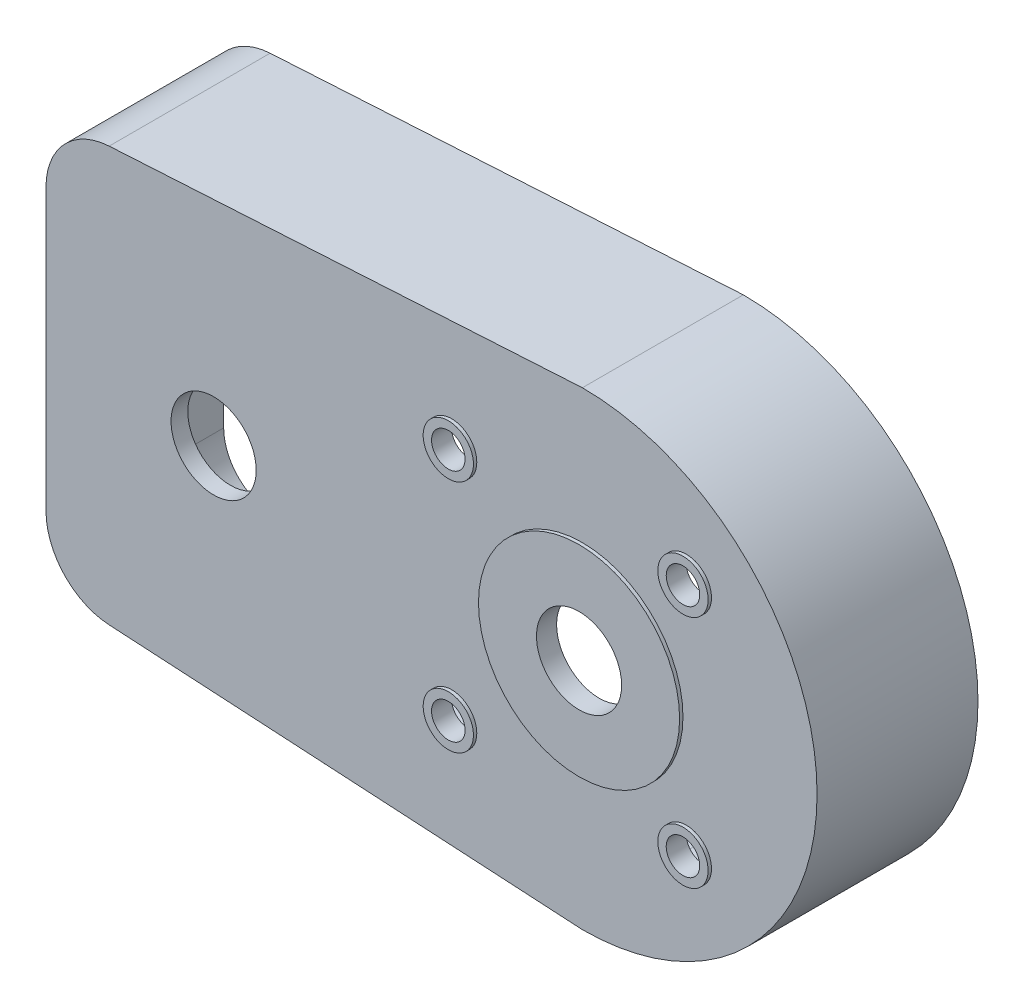
SolidWorks part; units mm, degrees
ref_plane "Front Plane" through (0, 0, 0) normal (0, 0, 1) x (1, 0, 0)
ref_plane "Top Plane" through (0, 0, 0) normal (0, 1, 0) x (1, 0, 0)
ref_plane "Right Plane" through (0, 0, 0) normal (1, 0, 0) x (0, 0, -1)
sketch "Sketch1" plane through (0, 0, 0) normal (0, 0, 1) x (1, 0, 0)
  line L0 (0, 0) -> (230, 0) construction
  line L1 (160, 52.3684) -> (160, -88.6842) construction
  line L2 (0, 41.8729) -> (0, -41.8729)
  line L3 (18.8457, 61.8395) -> (160, 70)
  line L4 (18.8457, -61.8395) -> (160, -70)
  arc A0 (160, -70) -> (160, 70) centre (160, 0) ccw
  arc A1 (18.8457, 61.8395) -> (0, 41.8729) centre (20, 41.8729) ccw
  arc A2 (18.8457, -61.8395) -> (0, -41.8729) centre (20, -41.8729) cw
  point P12 (0, 60.75)
  point P15 (0, -60.75)
  dimension "D4" = 20
  dimension "D5" = 20
  dimension "D1" = 230
  dimension "D2" = 70
  dimension "D3" = 121.5
extrude "Boss-Extrude1" add sketch "Sketch1" along normal mid plane 48 contours L3 A0 L4 A2 L2 A1
sketch "Sketch2" plane through (0, 0, -24) normal (0, 0, -1) x (-1, 0, 0)
  line L6 (-19.1343, 56.8479) -> (-160.1417, 64.9998)
  line L7 (-160.1417, -64.9998) -> (-19.1343, -56.8479)
  line L8 (-5, -41.8729) -> (-5, 41.8729)
  line L9 (-19.1343, 56.8479) -> (-160.1417, 64.9998)
  line L10 (-160.1417, -64.9998) -> (-19.1343, -56.8479)
  line L11 (-5, -41.8729) -> (-5, 41.8729)
  arc A6 (-5, 41.8729) -> (-19.1343, 56.8479) centre (-20, 41.8729) ccw
  arc A7 (-160.1417, 64.9998) -> (-160.1417, -64.9998) centre (-160, 0) ccw
  arc A8 (-19.1343, -56.8479) -> (-5, -41.8729) centre (-20, -41.8729) ccw
  arc A9 (-5, 41.8729) -> (-19.1343, 56.8479) centre (-20, 41.8729) ccw
  arc A10 (-160.1417, 64.9998) -> (-160.1417, -64.9998) centre (-160, 0) ccw
  arc A11 (-19.1343, -56.8479) -> (-5, -41.8729) centre (-20, -41.8729) ccw
  dimension "D1" = 5
extrude "Cut-Extrude1" cut sketch "Sketch2" against normal blind 43
sketch "Sketch4" plane through (0, 0, 24) normal (0, 0, 1) x (1, 0, 0)
  circle A0 centre (160, 0) radius 12.7
  dimension "D1" = 25.4
extrude "Cut-Extrude2" cut sketch "Sketch4" against normal blind 43
sketch "Sketch5" plane through (0, 0, 24) normal (0, 0, 1) x (1, 0, 0)
  line L0 (150.2143, 0) -> (267.5955, 0) construction
  line L1 (156, 0) -> (156, 90.9704) construction
  circle A0 centre (121, 35) radius 5
  circle A1 centre (191, 35) radius 5
  circle A2 centre (191, -35) radius 5
  circle A3 centre (121, -35) radius 5
  point P1 (160, 0)
  dimension "D3" = 10
  dimension "D1" = 70
  dimension "D2" = 70
extrude "Cut-Extrude3" cut sketch "Sketch5" against normal blind 43 contours A2 | A1 | A0 | A3
sketch "Sketch6" plane through (0, 0, 24) normal (0, 0, 1) x (1, 0, 0)
  line L0 (-16.671, 0) -> (247.1814, 0) construction
  line L1 (156, 0) -> (156, 96.1477) construction
  circle A0 centre (121, 35) radius 5
  circle A1 centre (121, 35) radius 7.5
  circle A2 centre (121, -35) radius 7.5
  circle A3 centre (121, -35) radius 5
  circle A4 centre (191, 35) radius 5
  circle A5 centre (191, 35) radius 7.5
  circle A6 centre (191, -35) radius 5
  circle A7 centre (191, -35) radius 7.5
  circle A8 centre (160, 0) radius 11
  circle A9 centre (160, 0) radius 30
  dimension "D1" = 15
  dimension "D2" = 60
extrude "Boss-Extrude2" add sketch "Sketch6" along normal mid plane 2
sketch "Sketch7" plane through (0, 0, 24) normal (0, 0, 1) x (1, 0, 0)
  circle A0 centre (50, 0) radius 12.7
  dimension "D1" = 25.4
  dimension "D2" = 50
extrude "Cut-Extrude4" cut sketch "Sketch7" against normal blind 10
sketch "Sketch8" plane through (0, 0, 23) normal (0, 0, -1) x (-1, 0, 0)
  circle A0 centre (-160, 0) radius 12.7 construction
  circle A1 centre (-160, 0) radius 12.7
extrude "Cut-Extrude5" cut sketch "Sketch8" against normal blind 10
